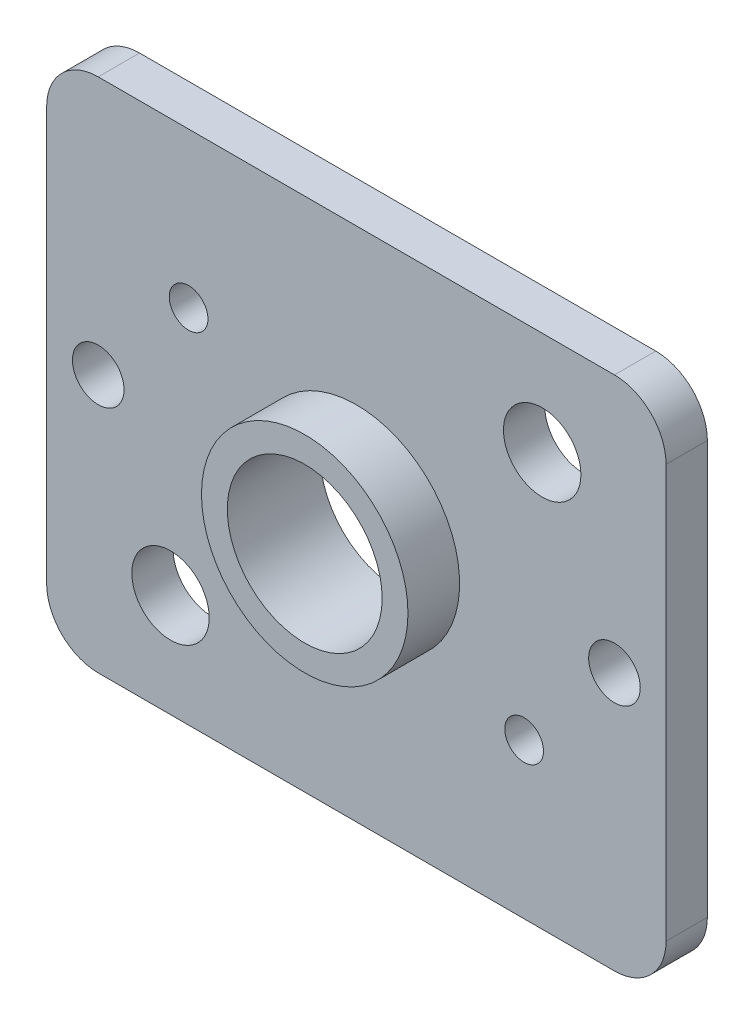
SolidWorks part; units mm, degrees
material "Латунь"
ref_plane "Спереди" through (0, 0, 0) normal (0, 0, 1) x (1, 0, 0)
ref_plane "Сверху" through (0, 0, 0) normal (0, 1, 0) x (1, 0, 0)
ref_plane "Справа" through (0, 0, 0) normal (1, 0, 0) x (0, 0, -1)
sketch "Эскиз1" plane through (0, 0, 0) normal (0, 0, 1) x (1, 0, 0)
  line L1 (-6, -5) -> (6, -5)
  line L2 (-6, -5) -> (-6, 5)
  line L3 (-6, 5) -> (6, 5)
  line L4 (6, -5) -> (6, 5)
  line L5 (-6, -5) -> (6, 5) construction
  line L6 (-6, 5) -> (6, -5) construction
  point P0 (0, 0)
  dimension "D1" = 12
  dimension "D2" = 10
extrude "Бобышка-Вытянуть1" add sketch "Эскиз1" along normal blind 0.8
sketch "Эскиз2" plane through (0, 0, 0.8) normal (0, 0, 1) x (1, 0, 0)
  line L0 (-6, -5) -> (6, 5) construction
  line L1 (-6, -5) -> (6, -5) construction
  line L2 (-6, 0) -> (6, 0) construction
  line L3 (-6, 5) -> (-6, -5) construction
  line L4 (6, 5) -> (-6, 5) construction
  line L5 (6, -5) -> (6, 5) construction
  circle A0 centre (0, 0) radius 1.5
  circle A1 centre (-3.6, -3) radius 0.75
  circle A2 centre (3.6, 3) radius 0.75
  circle A3 centre (3.25, -2) radius 0.375
  circle A4 centre (-3.25, 2) radius 0.375
  point P27 (0, 0)
  dimension "D1" = 3
  dimension "D3" = 1.5
  dimension "D5" = 1.5
  dimension "D8" = 0.75
  dimension "D9" = 2
  dimension "D10" = 0.75
  dimension "D11" = 2
  dimension "D2" = 2
  dimension "D4" = 2
  dimension "D6" = 2.75
  dimension "D7" = 3
extrude "Вырез-Вытянуть1" cut sketch "Эскиз2" against normal up to next
fillet "Скругление1" radius 1 4 edges at (6, -5, 0.4) (-6, -5, 0.4) (-6, 5, 0.4) (6, 5, 0.4)
sketch "Эскиз5" plane through (0, 0, 0.8) normal (0, 0, 1) x (1, 0, 0)
  line L1 (-6, 4) -> (-6, -4) construction
  line L3 (-6, 0) -> (6, 0) construction
  line L4 (6, -4) -> (6, 4) construction
  circle A0 centre (5, 0) radius 0.5
  circle A1 centre (-5, 0) radius 0.5
  dimension "D1" = 1
  dimension "D2" = 1
  dimension "D4" = 1
  dimension "D3" = 1
extrude "Вырез-Вытянуть2" cut sketch "Эскиз5" against normal through all
sketch "Эскиз14" plane through (0, 0, 0.8) normal (0, 0, 1) x (1, 0, 0)
  circle A0 centre (0, 0) radius 1.5 construction
  circle A1 centre (0, 0) radius 1.5
  circle A2 centre (0, 0) radius 2
  dimension "D1" = 0.5
extrude "Бобышка-Вытянуть2" add sketch "Эскиз14" along normal blind 1
